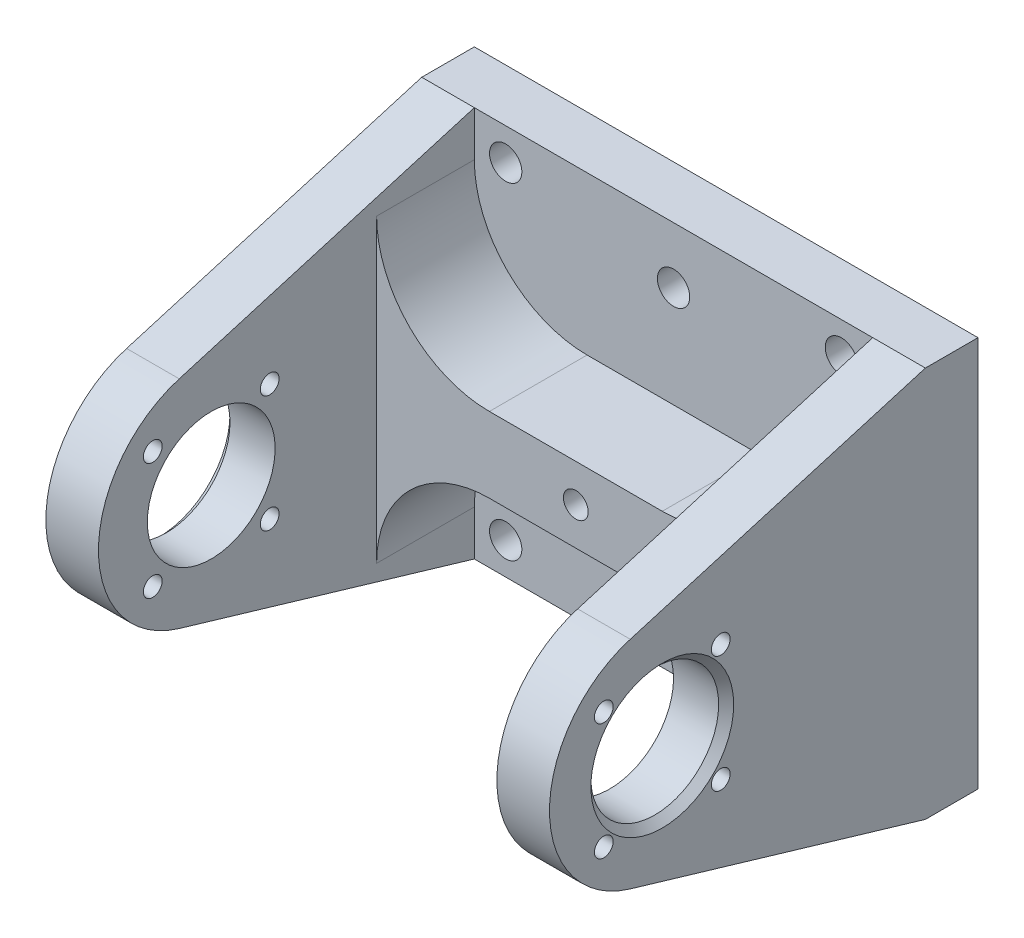
SolidWorks part; units mm, degrees
material "6061-T6 (SS)"
ref_plane "Front Plane" through (0, 0, 0) normal (0, 0, 1) x (1, 0, 0)
ref_plane "Top Plane" through (0, 0, 0) normal (0, 1, 0) x (1, 0, 0)
ref_plane "Right Plane" through (0, 0, 0) normal (1, 0, 0) x (0, 0, -1)
sketch "Sketch1" plane through (0, 0, 0) normal (1, 0, 0) x (0, 0, -1)
  line L0 (55, 0) -> (-55, 0) construction
  line L2 (0, 44.2539) -> (0, -44.2539) construction
  line L3 (-7, 26) -> (-46.2563, 14.3835)
  line L4 (-7, -26) -> (-46.2563, -14.3835)
  line L5 (-7, 26) -> (0, 26)
  line L6 (0, 26) -> (0, -26)
  line L7 (0, -26) -> (-7, -26)
  arc A0 (-46.2563, 14.3835) -> (-46.2563, -14.3835) centre (-42, 0) ccw
  circle A1 centre (-42, 0) radius 8.5
  point P1 (0, 0)
  dimension "D1" = 7
  dimension "D2" = 15
  dimension "D5" = 17
  dimension "D3" = 35
  dimension "D4" = 52
extrude "Boss-Extrude1" add sketch "Sketch1" along normal mid plane 67
sketch "Sketch2" plane through (0, 0, 0) normal (0, 1, 0) x (1, 0, 0)
  line L0 (0, -44.7868) -> (0, 44.7868) construction
  line L1 (-26.5, -57) -> (26.5, -57)
  line L2 (-26.5, -57) -> (-26.5, -7)
  line L3 (-26.5, -7) -> (26.5, -7)
  line L4 (26.5, -57) -> (26.5, -7)
  line L5 (-26.5, -57) -> (26.5, -7) construction
  line L6 (-26.5, -7) -> (26.5, -57) construction
  line L7 (33.5, -7) -> (-33.5, -7) construction
  line L8 (-33.5, -57) -> (33.5, -57) construction
  line L9 (-33.5, -46.2563) -> (-33.5, -57) construction
  point P0 (0, -32)
  dimension "D1" = 7
extrude "Cut-Extrude1" cut sketch "Sketch2" against normal mid plane 60
sketch "Sketch3" plane through (0, 0, 7) normal (0, 0, 1) x (1, 0, 0)
  line L0 (-26.5, -26) -> (-26.5, 26) construction
  line L1 (26.5, -5) -> (-26.5, -5)
  line L2 (26.5, -5) -> (26.5, 5)
  line L3 (26.5, 5) -> (-26.5, 5)
  line L4 (-26.5, -5) -> (-26.5, 5)
  line L5 (26.5, -5) -> (-26.5, 5) construction
  line L6 (26.5, 5) -> (-26.5, -5) construction
  point P0 (0, 0)
  dimension "D1" = 10
extrude "Boss-Extrude2" add sketch "Sketch3" along normal blind 13
fillet "Fillet1" radius 15 4 edges at (26.5, 5, 13.5) (26.5, -5, 13.5) (-26.5, -5, 13.5) (-26.5, 5, 13.5)
hole_wizard "CSK for M4 Countersunk Flat Head Screw1" positions "Sketch6" profile "Sketch7" countersink size "M4" standard "ISO" end condition through all
sketch "Sketch6" plane through (0, 0, 0) normal (0, 0, -1) x (-1, 0, 0)
  line L0 (0, 44.7868) -> (0, -44.7868) construction
  line L1 (0, 18.5) -> (0, -18.5) construction
  point P0 (0, 18.5)
  point P8 (0, -18.5)
  point P20 (0, 0)
  dimension "D1" = 37
sketch "Sketch7" plane through (0, 18.5, 0) normal (1, 0, 0) x (0, 1, 0)
  line L0 (0, 0) -> (0, 57)
  line L1 (0, 57) -> (2.15, 57)
  line L2 (2.15, 57) -> (2.15, 2.55)
  line L3 (2.15, 2.55) -> (4.7, 0)
  line L5 (4.7, 0) -> (0, 0)
  line L6 (-2.15, 2.55) -> (-4.7, 0) construction
  line L11 (0, -6.35) -> (0, 107.95) construction
  dimension "Thru Hole Dia." = 4.3
  dimension "Thru Hole Depth" = 57
  dimension "Near C'Sink Dia." = 9.4
  dimension "Near C'Sink Angle" = 90
hole_wizard "M4 Tapped Hole1" positions "Sketch8" profile "Sketch9" tap size "M4" standard "ISO" end condition through all
sketch "Sketch8" plane through (0, 0, 20) normal (0, 0, 1) x (1, 0, 0)
  point P0 (0, 0)
sketch "Sketch9" plane through (0, 0, 20) normal (1, 0, 0) x (0, -1, 0)
  line L0 (0, 0) -> (0, 20)
  line L1 (0, 20) -> (1.65, 20)
  line L2 (1.65, 20) -> (1.65, 0)
  line L5 (1.65, 0) -> (0, 0)
  line L11 (0, -6.35) -> (0, 107.95) construction
  dimension "Thru Tap Drill Dia." = 3.3
  dimension "Thru Tap Drill Depth" = 20
cosmetic thread "Hole Thread1" parameters "D2"=4
chamfer "Chamfer1" distance 1 angle 45 2 edges at (-33.5, 0, 33.5) (33.5, 0, 33.5)
hole_wizard "M3 Tapped Hole2" positions "Sketch12" profile "Sketch11" tap size "M3" standard "ISO"
sketch "Sketch12" plane through (33.5, 0, 0) normal (1, 0, 0) x (0, 0, -1)
  line L1 (-34.2218, -7.7782) -> (-49.7782, -7.7782) construction
  line L2 (-34.2218, -7.7782) -> (-34.2218, 7.7782) construction
  line L3 (-34.2218, 7.7782) -> (-49.7782, 7.7782) construction
  line L4 (-49.7782, -7.7782) -> (-49.7782, 7.7782) construction
  line L5 (-34.2218, -7.7782) -> (-49.7782, 7.7782) construction
  line L6 (-34.2218, 7.7782) -> (-49.7782, -7.7782) construction
  circle A0 centre (-42, 0) radius 11 construction
  point P0 (-34.2218, 7.7782)
  point P8 (-49.7782, 7.7782)
  point P11 (-34.2218, -7.7782)
  point P13 (-49.7782, -7.7782)
  dimension "D1" = 22
sketch "Sketch11" plane through (33.5, 7.7782, 34.2218) normal (0, 1, 0) x (0, 0, -1)
  line L0 (0, 0) -> (0, 7)
  line L1 (0, 7) -> (1.25, 7)
  line L2 (1.25, 7) -> (1.25, 0)
  line L5 (1.25, 0) -> (0, 0)
  line L11 (0, -6.35) -> (0, 107.95) construction
  dimension "Thru Tap Drill Dia." = 2.5
  dimension "Thru Tap Drill Depth" = 7
cosmetic thread "Hole Thread2" parameters "D2"=3
cosmetic thread "Hole Thread3" parameters "D2"=3
cosmetic thread "Hole Thread4" parameters "D2"=3
cosmetic thread "Hole Thread5" parameters "D2"=3
mirror "Mirror1" about plane through (0, 0, 0) normal (1, 0, 0) of "M3 Tapped Hole2"
cosmetic thread "Hole Thread6" parameters "D2"=3
cosmetic thread "Hole Thread7" parameters "D2"=3
cosmetic thread "Hole Thread8" parameters "D2"=3
cosmetic thread "Hole Thread9" parameters "D2"=3
hole_wizard "M4 Tapped Hole2" positions "Sketch13" profile "Sketch14" tap size "M4" standard "ISO"
sketch "Sketch13" plane through (0, 0, 0) normal (0, 0, -1) x (-1, 0, 0)
  line L0 (-30, 20) -> (30, -20) construction
  line L2 (-30, -20) -> (30, 20) construction
  line L4 (33.5, -26) -> (33.5, 26) construction
  line L5 (-33.5, 26) -> (33.5, 26) construction
  point P0 (-30, 20)
  point P2 (-30, -20)
  point P4 (30, 20)
  point P6 (30, -20)
  point P39 (-30, 0)
  point P41 (30, 0)
  dimension "D1" = 3.5
  dimension "D2" = 40
cosmetic thread "Hole Thread10" parameters "D1"=12, "D2"=4
cosmetic thread "Hole Thread11" parameters "D1"=12, "D2"=4
cosmetic thread "Hole Thread12" parameters "D1"=12, "D2"=4
cosmetic thread "Hole Thread13" parameters "D1"=12, "D2"=4
sketch "Sketch14" plane through (30, 20, 0) normal (1, 0, 0) x (0, 1, 0)
  line L0 (0, 0) -> (0, 16.9914)
  line L1 (0, 16.9914) -> (1.65, 16)
  line L2 (1.65, 16) -> (1.65, 0)
  line L5 (1.65, 0) -> (0, 0)
  line L10 (0, 16.9914) -> (-1.65, 16) construction
  line L11 (0, -6.35) -> (0, 107.95) construction
  dimension "Tap Drill Dia." = 3.3
  dimension "Tap Drill Depth" = 16
  dimension "Drill Angle" = 118
cosmetic thread "Hole Thread18" parameters "D1"=12, "D2"=4
cosmetic thread "Hole Thread19" parameters "D1"=12, "D2"=4
hole_wizard "M4 Clearance Hole1" positions "Sketch17" profile "Sketch18" hole size "M4" standard "ISO" end condition through all
sketch "Sketch17" plane through (0, 0, 0) normal (0, 0, -1) x (-1, 0, 0)
  line L1 (22.33, -21.75) -> (-22.33, -21.75) construction
  line L2 (22.33, -21.75) -> (22.33, 21.75) construction
  line L3 (22.33, 21.75) -> (-22.33, 21.75) construction
  line L4 (-22.33, -21.75) -> (-22.33, 21.75) construction
  line L5 (22.33, -21.75) -> (-22.33, 21.75) construction
  line L6 (22.33, 21.75) -> (-22.33, -21.75) construction
  point P0 (-22.33, 21.75)
  point P7 (22.33, -21.75)
  point P8 (22.33, 21.75)
  point P9 (-22.33, -21.75)
  dimension "D1" = 43.5
  dimension "D2" = 44.66
sketch "Sketch18" plane through (22.33, 21.75, 0) normal (1, 0, 0) x (0, 1, 0)
  line L0 (0, 0) -> (0, 57)
  line L1 (0, 57) -> (2.15, 57)
  line L2 (2.15, 57) -> (2.15, 0)
  line L5 (2.15, 0) -> (0, 0)
  line L11 (0, -6.35) -> (0, 107.95) construction
  dimension "Thru Hole Dia." = 4.3
  dimension "Thru Hole Depth" = 57
